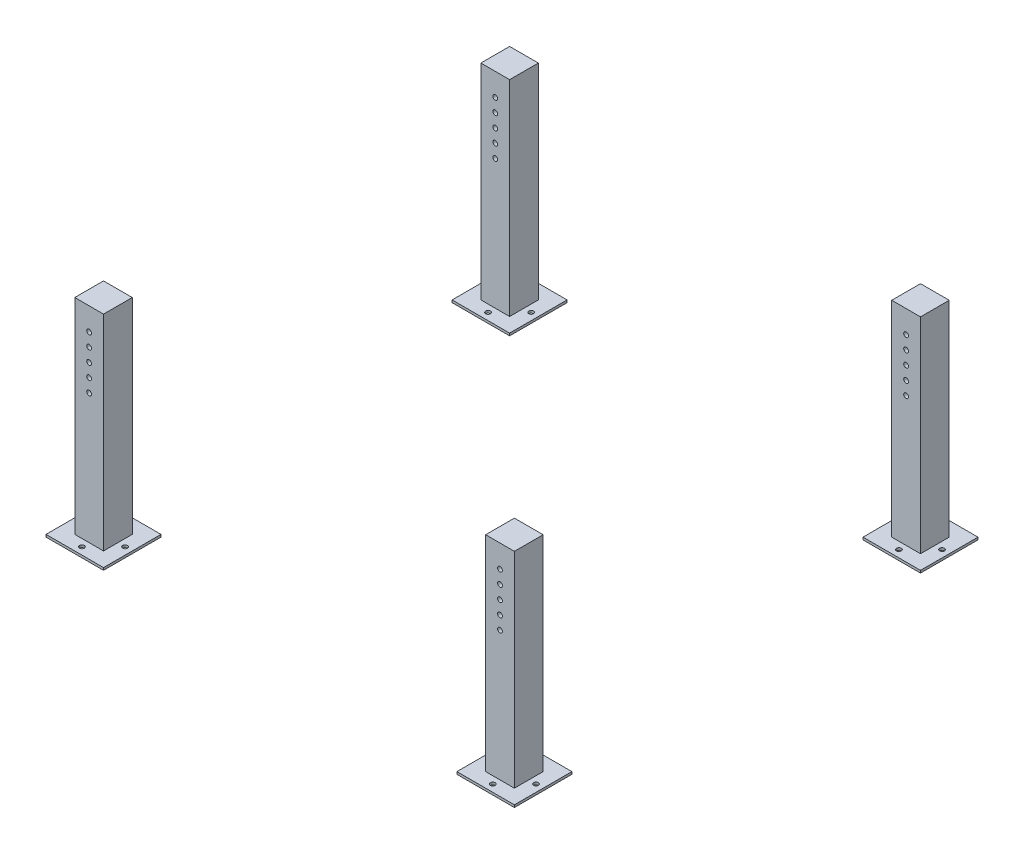
SolidWorks part; units mm, degrees
ref_plane "Alzado" through (0, 0, 0) normal (0, 0, 1) x (1, 0, 0)
ref_plane "Planta" through (0, 0, 0) normal (0, 1, 0) x (1, 0, 0)
ref_plane "Vista lateral" through (0, 0, 0) normal (1, 0, 0) x (0, 0, -1)
sketch "Croquis1" plane through (0, 0, 0) normal (0, 1, 0) x (1, 0, 0)
  line L0 (76.2, 0) -> (1088.87, 0) construction
  line L1 (0, 0) -> (76.2, 0)
  line L2 (0, 0) -> (0, -76.2)
  line L3 (0, -76.2) -> (76.2, -76.2)
  line L4 (76.2, 0) -> (76.2, -76.2)
  line L5 (0, -76.2) -> (0, -576.2) construction
  line L6 (1088.87, 0) -> (1165.07, 0)
  line L7 (1088.87, 0) -> (1088.87, -76.2)
  line L8 (1088.87, -76.2) -> (1165.07, -76.2)
  line L9 (1165.07, 0) -> (1165.07, -76.2)
  line L10 (0, -576.2) -> (329.6526, -576.2) construction
  line L11 (76.2, -1152.4) -> (1088.87, -1152.4) construction
  line L12 (1165.07, -1152.4) -> (1165.07, -1076.2)
  line L13 (1088.87, -1076.2) -> (1165.07, -1076.2)
  line L14 (1088.87, -1152.4) -> (1088.87, -1076.2)
  line L15 (1088.87, -1152.4) -> (1165.07, -1152.4)
  line L16 (76.2, -1152.4) -> (76.2, -1076.2)
  line L17 (0, -1076.2) -> (76.2, -1076.2)
  line L18 (0, -1152.4) -> (0, -1076.2)
  line L19 (0, -1152.4) -> (76.2, -1152.4)
  point P19 (38.1, 0)
  point P20 (1126.97, 0)
  point P21 (0, -38.1)
  point P22 (0, -1114.3)
  dimension "D1" = 76.2
  dimension "D2" = 76.2
  dimension "D3" = 76.2
  dimension "D4" = 76.2
  dimension "D5" = 1012.67
  dimension "D6" = 500
  dimension "D7" = 1088.87
  dimension "D8" = 1076.2
extrude "Saliente-Extruir1" add sketch "Croquis1" along normal blind 550
sketch "Croquis2" plane through (0, 0, 0) normal (0, -1, 0) x (1, 0, 0)
  line L0 (38.1, 0) -> (38.1, 76.2) construction
  line L1 (0, 0) -> (76.2, 0)
  line L2 (0, 0) -> (0, 76.2)
  line L3 (0, 76.2) -> (76.2, 76.2)
  line L4 (76.2, 0) -> (76.2, 76.2)
  line L5 (1126.97, 0) -> (1126.97, 76.2) construction
  line L6 (-38.1, 114.3) -> (114.3, 114.3)
  line L7 (-38.1, 114.3) -> (-38.1, -38.1)
  line L8 (-38.1, -38.1) -> (114.3, -38.1)
  line L9 (114.3, 114.3) -> (114.3, -38.1)
  line L10 (-38.1, 114.3) -> (114.3, -38.1) construction
  line L11 (-38.1, -38.1) -> (114.3, 114.3) construction
  line L12 (1088.87, 0) -> (1165.07, 0)
  line L13 (1088.87, 0) -> (1088.87, 76.2)
  line L14 (1088.87, 76.2) -> (1165.07, 76.2)
  line L15 (1165.07, 0) -> (1165.07, 76.2)
  line L16 (1126.97, 1076.2) -> (1126.97, 1152.4) construction
  line L17 (1203.17, 114.3) -> (1050.77, 114.3)
  line L18 (1203.17, 114.3) -> (1203.17, -38.1)
  line L19 (1203.17, -38.1) -> (1050.77, -38.1)
  line L20 (1050.77, 114.3) -> (1050.77, -38.1)
  line L21 (1203.17, 114.3) -> (1050.77, -38.1) construction
  line L22 (1203.17, -38.1) -> (1050.77, 114.3) construction
  line L23 (1088.87, 1076.2) -> (1165.07, 1076.2)
  line L24 (1088.87, 1076.2) -> (1088.87, 1152.4)
  line L25 (1088.87, 1152.4) -> (1165.07, 1152.4)
  line L26 (1165.07, 1076.2) -> (1165.07, 1152.4)
  line L27 (38.1, 1076.2) -> (38.1, 1152.4) construction
  line L28 (1203.17, 1190.5) -> (1050.77, 1190.5)
  line L29 (1203.17, 1190.5) -> (1203.17, 1038.1)
  line L30 (1203.17, 1038.1) -> (1050.77, 1038.1)
  line L31 (1050.77, 1190.5) -> (1050.77, 1038.1)
  line L32 (1203.17, 1190.5) -> (1050.77, 1038.1) construction
  line L33 (1203.17, 1038.1) -> (1050.77, 1190.5) construction
  line L34 (0, 1076.2) -> (76.2, 1076.2)
  line L35 (0, 1076.2) -> (0, 1152.4)
  line L36 (0, 1152.4) -> (76.2, 1152.4)
  line L37 (76.2, 1076.2) -> (76.2, 1152.4)
  line L39 (-38.1, 1190.5) -> (114.3, 1190.5)
  line L40 (-38.1, 1190.5) -> (-38.1, 1038.1)
  line L41 (-38.1, 1038.1) -> (114.3, 1038.1)
  line L42 (114.3, 1190.5) -> (114.3, 1038.1)
  line L43 (-38.1, 1190.5) -> (114.3, 1038.1) construction
  line L44 (-38.1, 1038.1) -> (114.3, 1190.5) construction
  point P8 (38.1, 38.1)
  point P21 (1126.97, 38.1)
  point P34 (1126.97, 1114.3)
  point P47 (38.1, 1114.3)
  dimension "D1" = 38.1
  dimension "D2" = 38.1
  dimension "D3" = 38.1
  dimension "D4" = 38.1
  dimension "D5" = 38.1
  dimension "D6" = 38.1
  dimension "D7" = 38.1
  dimension "D8" = 38.1
extrude "Saliente-Extruir2" add sketch "Croquis2" against normal blind 6.35
sketch "Croquis3" plane through (0, 6.35, 0) normal (0, 1, 0) x (1, 0, 0)
  line L0 (38.1, 38.1) -> (38.1, 0) construction
  line L1 (-38.1, 38.1) -> (114.3, 38.1) construction
  line L2 (0, 0) -> (76.2, 0) construction
  line L3 (-38.1, 38.1) -> (0, 0) construction
  line L4 (38.1, 0) -> (38.1, -38.1) construction
  line L5 (38.1, -38.1) -> (0, -38.1) construction
  line L6 (0, 0) -> (0, -76.2) construction
  circle A0 centre (38.1, 19.05) radius 6.35
  circle A1 centre (-19.05, -38.1) radius 6.35
  circle A2 centre (38.1, -95.25) radius 6.35
  circle A3 centre (95.25, -38.1) radius 6.35
  dimension "D1" = 12.7
extrude "Cortar-Extruir1" cut sketch "Croquis3" against normal blind 6.35
sketch "Croquis4" plane through (0, 6.35, 0) normal (0, 1, 0) x (1, 0, 0)
  line L0 (1126.97, 38.1) -> (1126.97, 0) construction
  line L1 (1050.77, 38.1) -> (1203.17, 38.1) construction
  line L2 (1088.87, 0) -> (1165.07, 0) construction
  line L3 (1050.77, 38.1) -> (1088.87, 0) construction
  line L4 (1126.97, 0) -> (1126.97, -38.1) construction
  line L5 (1126.97, -38.1) -> (1088.87, -38.1) construction
  line L6 (1088.87, -76.2) -> (1088.87, 0) construction
  circle A0 centre (1126.97, 19.05) radius 6.35
  circle A1 centre (1069.82, -38.1) radius 6.35
  circle A2 centre (1126.97, -95.25) radius 6.35
  circle A3 centre (1184.12, -38.1) radius 6.35
  dimension "D1" = 12.7
extrude "Cortar-Extruir2" cut sketch "Croquis4" against normal blind 6.35
sketch "Croquis5" plane through (0, 6.35, 0) normal (0, 1, 0) x (1, 0, 0)
  line L0 (1126.97, -1038.1) -> (1126.97, -1076.2) construction
  line L1 (1050.77, -1038.1) -> (1203.17, -1038.1) construction
  line L2 (1165.07, -1076.2) -> (1088.87, -1076.2) construction
  line L3 (1050.77, -1038.1) -> (1088.87, -1076.2) construction
  line L4 (1126.97, -1076.2) -> (1126.97, -1114.3) construction
  line L5 (1126.97, -1114.3) -> (1088.87, -1114.3) construction
  line L6 (1088.87, -1152.4) -> (1088.87, -1076.2) construction
  circle A0 centre (1126.97, -1057.15) radius 6.35
  circle A1 centre (1069.82, -1114.3) radius 6.35
  circle A2 centre (1126.97, -1171.45) radius 6.35
  circle A3 centre (1184.12, -1114.3) radius 6.35
  dimension "D1" = 12.7
extrude "Cortar-Extruir3" cut sketch "Croquis5" against normal blind 6.35
sketch "Croquis6" plane through (0, 6.35, 0) normal (0, 1, 0) x (1, 0, 0)
  line L0 (38.1, -1038.1) -> (38.1, -1076.2) construction
  line L1 (-38.1, -1038.1) -> (114.3, -1038.1) construction
  line L2 (76.2, -1076.2) -> (0, -1076.2) construction
  line L3 (-38.1, -1038.1) -> (0, -1076.2) construction
  line L4 (38.1, -1076.2) -> (38.1, -1114.3) construction
  line L5 (38.1, -1114.3) -> (0, -1114.3) construction
  line L6 (0, -1076.2) -> (0, -1152.4) construction
  circle A0 centre (38.1, -1057.15) radius 6.35
  circle A1 centre (-19.05, -1114.3) radius 6.35
  circle A2 centre (38.1, -1171.45) radius 6.35
  circle A3 centre (95.25, -1114.3) radius 6.35
  dimension "D1" = 12.7
extrude "Cortar-Extruir4" cut sketch "Croquis6" against normal blind 6.35
sketch "Croquis7" plane through (0, 0, 1152.4) normal (0, 0, 1) x (1, 0, 0)
  line L0 (38.1, 550) -> (38.1, 490) construction
  line L1 (0, 550) -> (76.2, 550) construction
  line L2 (38.1, 490) -> (38.1, 455) construction
  line L3 (38.1, 455) -> (38.1, 420) construction
  line L4 (38.1, 420) -> (38.1, 385) construction
  line L5 (38.1, 385) -> (38.1, 350) construction
  circle A0 centre (38.1, 490) radius 6.35
  circle A1 centre (38.1, 455) radius 6.35
  circle A2 centre (38.1, 420) radius 6.35
  circle A3 centre (38.1, 385) radius 6.35
  circle A4 centre (38.1, 350) radius 6.35
  dimension "D2" = 12.7
  dimension "D4" = 12.7
  dimension "D6" = 12.7
  dimension "D8" = 12.7
  dimension "D10" = 12.7
  dimension "D1" = 60
  dimension "D3" = 35
  dimension "D5" = 35
  dimension "D7" = 35
  dimension "D9" = 35
extrude "Cortar-Extruir5" cut sketch "Croquis7" against normal up to surface (76.2 mm away) up to face at (38.1, 278.175, 1076.2)
sketch "Croquis8" plane through (0, 0, 1152.4) normal (0, 0, 1) x (1, 0, 0)
  line L0 (1126.97, 550) -> (1126.97, 490) construction
  line L1 (1088.87, 550) -> (1165.07, 550) construction
  line L2 (1126.97, 490) -> (1126.97, 455) construction
  line L3 (1126.97, 455) -> (1126.97, 420) construction
  line L4 (1126.97, 420) -> (1126.97, 385) construction
  line L5 (1126.97, 385) -> (1126.97, 350) construction
  circle A0 centre (1126.97, 490) radius 6.35
  circle A1 centre (1126.97, 455) radius 6.35
  circle A2 centre (1126.97, 420) radius 6.35
  circle A3 centre (1126.97, 385) radius 6.35
  circle A4 centre (1126.97, 350) radius 6.35
  dimension "D6" = 12.7
  dimension "D7" = 12.7
  dimension "D8" = 12.7
  dimension "D9" = 12.7
  dimension "D10" = 12.7
  dimension "D1" = 60
  dimension "D2" = 35
  dimension "D3" = 35
  dimension "D4" = 35
  dimension "D5" = 35
extrude "Cortar-Extruir6" cut sketch "Croquis8" against normal up to surface (76.2 mm away) up to face at (1126.97, 278.175, 1076.2)
sketch "Croquis9" plane through (0, 0, 0) normal (0, 0, -1) x (-1, 0, 0)
  circle A0 centre (-1126.97, 490) radius 6.35
  circle A1 centre (-1126.97, 455) radius 6.35
  circle A2 centre (-1126.97, 420) radius 6.35
  circle A3 centre (-1126.97, 385) radius 6.35
  circle A4 centre (-1126.97, 350) radius 6.35
extrude "Cortar-Extruir7" cut sketch "Croquis9" against normal up to surface (76.2 mm away) up to face at (1126.97, 278.175, 76.2)
sketch "Croquis10" plane through (0, 0, 0) normal (0, 0, -1) x (-1, 0, 0)
  circle A0 centre (-38.1, 490) radius 6.35
  circle A1 centre (-38.1, 455) radius 6.35
  circle A2 centre (-38.1, 420) radius 6.35
  circle A3 centre (-38.1, 385) radius 6.35
  circle A4 centre (-38.1, 350) radius 6.35
extrude "Cortar-Extruir8" cut sketch "Croquis10" against normal up to surface (76.2 mm away) up to face at (38.1, 278.175, 76.2)
